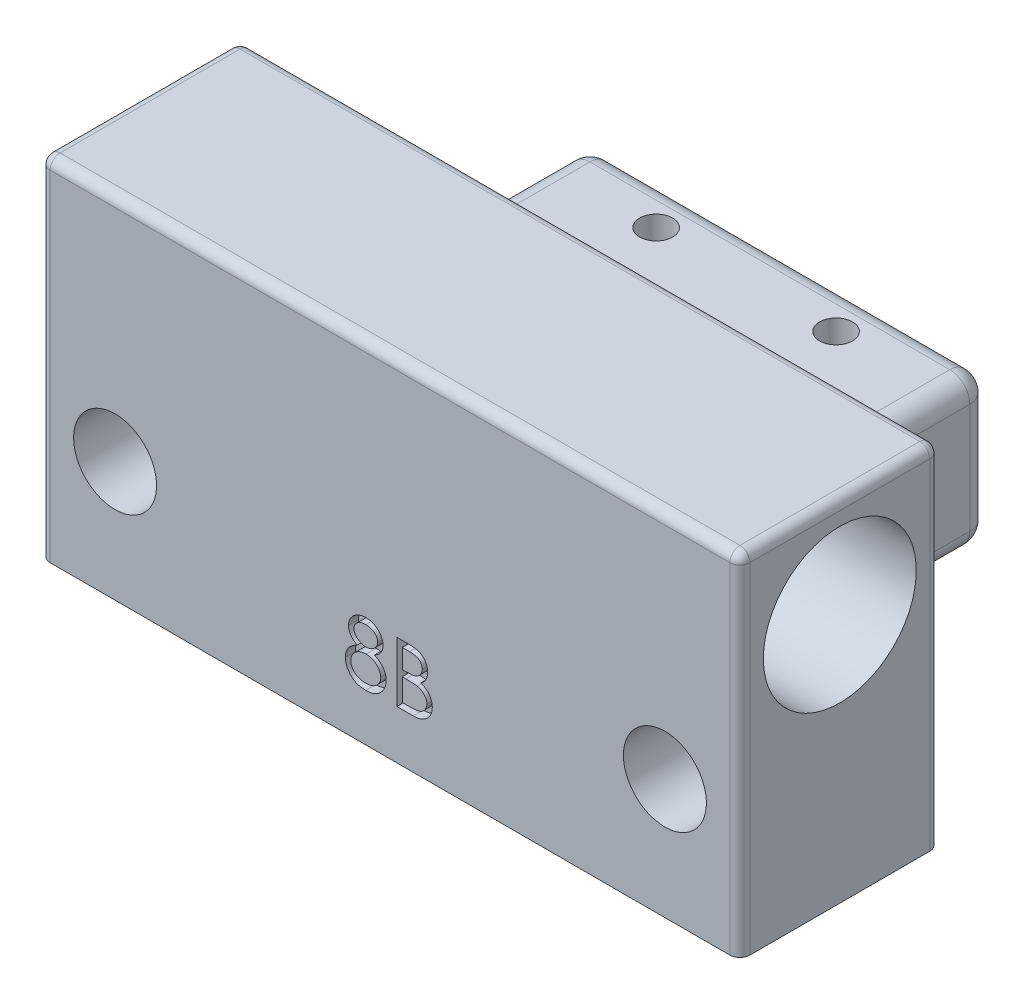
SolidWorks part; units mm, degrees
ref_plane "Alzado" through (0, 0, 0) normal (0, 0, 1) x (1, 0, 0)
ref_plane "Planta" through (0, 0, 0) normal (0, 1, 0) x (1, 0, 0)
ref_plane "Vista lateral" through (0, 0, 0) normal (1, 0, 0) x (0, 0, -1)
sketch "Croquis1" plane through (0, 0, 0) normal (0, 1, 0) x (1, 0, 0)
  line L1 (-35, -10) -> (35, -10)
  line L2 (-35, -10) -> (-35, 10)
  line L3 (-35, 10) -> (35, 10)
  line L4 (35, -10) -> (35, 10)
  line L5 (-35, -10) -> (35, 10) construction
  line L6 (-35, 10) -> (35, -10) construction
  point P0 (0, 0)
extrude "Saliente-Extruir1" add sketch "Croquis1" along normal blind 35
sketch "Croquis2" plane through (-35, 0, 0) normal (-1, 0, 0) x (0, 0, 1)
  line L0 (-10, 35) -> (0, 35) construction
  line L1 (-10, 35) -> (10, 35) construction
  line L2 (0, 35) -> (0, 25) construction
  circle A0 centre (0, 25) radius 7.65
extrude "Cortar-Extruir1" cut sketch "Croquis2" against normal through all
sketch "Croquis3" plane through (0, 0, -10) normal (0, 0, -1) x (-1, 0, 0)
  line L0 (-35, 0) -> (-27.5, 0) construction
  line L1 (-35, 0) -> (35, 0) construction
  line L2 (-27.5, 0) -> (-27.5, 12) construction
  line L3 (35, 0) -> (27.5, 0) construction
  line L4 (27.5, 0) -> (27.5, 12) construction
  circle A0 centre (-27.5, 12) radius 4.15
  circle A1 centre (27.5, 12) radius 4.15
extrude "Cortar-Extruir2" cut sketch "Croquis3" against normal through all
fillet "Redondeo1" radius 1 8 edges at (-35, 17.5, 10) (-35, 17.5, -10) (-35, 35, 0) (35, 17.5, 10) (0, 35, -10) (0, 35, 10) (35, 35, 0) (35, 17.5, -10)
sketch "Croquis5" plane through (0, 0, -10) normal (0, 0, -1) x (-1, 0, 0)
  line L0 (0, 0) -> (0, 8.7232) construction
  line L1 (-34, 0) -> (34, 0) construction
  line L3 (0, 8.7232) -> (0, 26) construction
  line L4 (0, 26) -> (20, 26) construction
  line L5 (20, 26) -> (20, 8.7232) construction
  line L6 (20, 8.7232) -> (-20, 8.7232) construction
  line L7 (-20, 8.7232) -> (-20, 23.7232) construction
  line L9 (20, 8.7232) -> (-20, 8.7232)
  line L10 (20, 8.7232) -> (20, 23.7232)
  line L11 (20, 23.7232) -> (-20, 23.7232)
  line L12 (-20, 8.7232) -> (-20, 23.7232)
  dimension "D1" = 8.7232
  dimension "D2" = 15
extrude "Saliente-Extruir3" add sketch "Croquis5" along normal blind 20
fillet "Redondeo3" radius 2 12 edges at (0, 8.7232, -10) (20, 8.7232, -20) (20, 16.2232, -10) (20, 23.7232, -20) (-20, 8.7232, -20) (0, 8.7232, -30) (20, 16.2232, -30) (0, 23.7232, -10) (-20, 23.7232, -20) (0, 23.7232, -30) (-20, 16.2232, -30) (-20, 16.2232, -10)
sketch "Croquis6" plane through (0, 23.7232, 0) normal (0, 1, 0) x (1, 0, 0)
  line L0 (18, 12) -> (18, 28) construction
  line L1 (-18, 12) -> (18, 12) construction
  line L2 (18, 28) -> (-18, 28) construction
  line L3 (0, 12) -> (0, 28) construction
  circle A0 centre (9, 14.375) radius 1.65
  circle A1 centre (9, 25.625) radius 1.65
  circle A2 centre (-9, 25.625) radius 1.65
  circle A3 centre (-9, 14.375) radius 1.65
  dimension "D1" = 9
  dimension "D2" = 9
  dimension "D3" = 2.375
  dimension "D4" = 2.375
extrude "Cortar-Extruir3" cut sketch "Croquis6" against normal up to next
sketch "Croquis7" plane through (0, 0, 10) normal (0, 0, 1) x (1, 0, 0)
  line L0 (-34, 4.8864) -> (34, 4.8864) construction
  line L1 (-34, 34) -> (-34, 0) construction
  line L2 (34, 0) -> (34, 34) construction
  text T0 "8B" font "Century Gothic" height 6
extrude "Cortar-Extruir4" cut sketch "Croquis7" against normal blind 1
